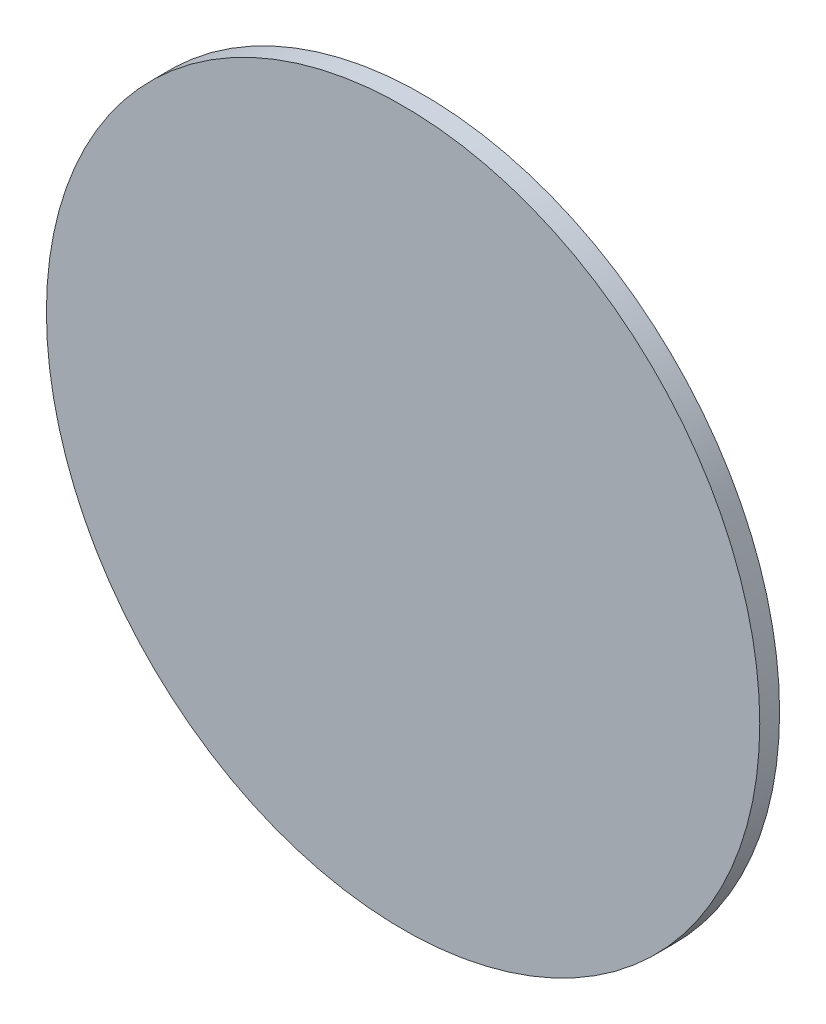
SolidWorks part; units mm, degrees
ref_plane "Front Plane" through (0, 0, 0) normal (0, 0, 1) x (1, 0, 0)
ref_plane "Top Plane" through (0, 0, 0) normal (0, 1, 0) x (1, 0, 0)
ref_plane "Right Plane" through (0, 0, 0) normal (1, 0, 0) x (0, 0, -1)
sketch "Sketch1" plane through (0, 0, 0) normal (0, 0, 1) x (1, 0, 0)
  line L0 (580.6612, 224.8388) -> (598.3388, 207.1612) construction
  line L1 (598.3388, 207.1612) -> (589.5, 216) construction
  line L2 (589.5, 216) -> (589.5, 151) construction
  circle A0 centre (589.5, 151) radius 90
  circle A1 centre (580.6612, 224.8388) radius 1.5
  circle A2 centre (589.5, 216) radius 1.5
  circle A3 centre (598.3388, 207.1612) radius 1.5
  circle A4 centre (606.4486, 223.4089) radius 1.5
  circle A5 centre (611.7313, 212.08) radius 1.5
  circle A6 centre (617.014, 200.7512) radius 1.5
  circle A7 centre (630.1917, 213.2453) radius 1.5
  circle A8 centre (631.2812, 200.7929) radius 1.5
  circle A9 centre (632.3706, 188.3405) radius 1.5
  circle A10 centre (649.0269, 195.5741) radius 1.5
  circle A11 centre (645.7917, 183.5) radius 1.5
  circle A12 centre (642.5564, 171.4259) radius 1.5
  circle A13 centre (660.6822, 172.5265) radius 1.5
  circle A14 centre (653.5125, 162.2871) radius 1.5
  circle A15 centre (646.3428, 152.0477) radius 1.5
  circle A16 centre (663.7519, 146.8826) radius 1.5
  circle A17 centre (653.5125, 139.7129) radius 1.5
  circle A18 centre (643.2731, 132.5432) radius 1.5
  circle A19 centre (657.8657, 121.7352) radius 1.5
  circle A20 centre (645.7917, 118.5) radius 1.5
  circle A21 centre (633.7176, 115.2648) radius 1.5
  circle A22 centre (643.7336, 100.1177) radius 1.5
  circle A23 centre (631.2812, 101.2071) radius 1.5
  circle A24 centre (618.8288, 102.2966) radius 1.5
  circle A25 centre (623.0602, 84.6373) radius 1.5
  circle A26 centre (611.7313, 89.92) radius 1.5
  circle A27 centre (600.4025, 95.2027) radius 1.5
  circle A28 centre (598.3388, 77.1612) radius 1.5
  circle A29 centre (589.5, 86) radius 1.5
  circle A30 centre (580.6612, 94.8388) radius 1.5
  circle A31 centre (572.5514, 78.5911) radius 1.5
  circle A32 centre (567.2687, 89.92) radius 1.5
  circle A33 centre (561.986, 101.2488) radius 1.5
  circle A34 centre (548.8083, 88.7547) radius 1.5
  circle A35 centre (547.7188, 101.2071) radius 1.5
  circle A36 centre (546.6294, 113.6595) radius 1.5
  circle A37 centre (529.9731, 106.4259) radius 1.5
  circle A38 centre (533.2083, 118.5) radius 1.5
  circle A39 centre (536.4436, 130.5741) radius 1.5
  circle A40 centre (518.3178, 129.4735) radius 1.5
  circle A41 centre (525.4875, 139.7129) radius 1.5
  circle A42 centre (532.6572, 149.9523) radius 1.5
  circle A43 centre (515.2481, 155.1174) radius 1.5
  circle A44 centre (525.4875, 162.2871) radius 1.5
  circle A45 centre (535.7269, 169.4568) radius 1.5
  circle A46 centre (521.1343, 180.2648) radius 1.5
  circle A47 centre (533.2083, 183.5) radius 1.5
  circle A48 centre (545.2824, 186.7352) radius 1.5
  circle A49 centre (535.2664, 201.8823) radius 1.5
  circle A50 centre (547.7188, 200.7929) radius 1.5
  circle A51 centre (560.1712, 199.7034) radius 1.5
  circle A52 centre (555.9398, 217.3627) radius 1.5
  circle A53 centre (567.2687, 212.08) radius 1.5
  circle A54 centre (578.5975, 206.7973) radius 1.5
  point P114 (589.5, 151)
  dimension "D1" = 180
  dimension "D5" = 3
  dimension "D2" = 65
  dimension "D3" = 45
  dimension "D4" = 25
  dimension "D6" = 18
extrude "Boss-Extrude1" add sketch "Sketch1" along normal blind 5
sketch "Sketch2" plane through (0, 0, 5) normal (0, 0, 1) x (1, 0, 0)
  circle A1 centre (589.5, 151) radius 90
  circle A2 centre (589.5, 151) radius 90
  dimension "D1" = 0
extrude "Boss-Extrude2" add sketch "Sketch2" against normal blind 5
